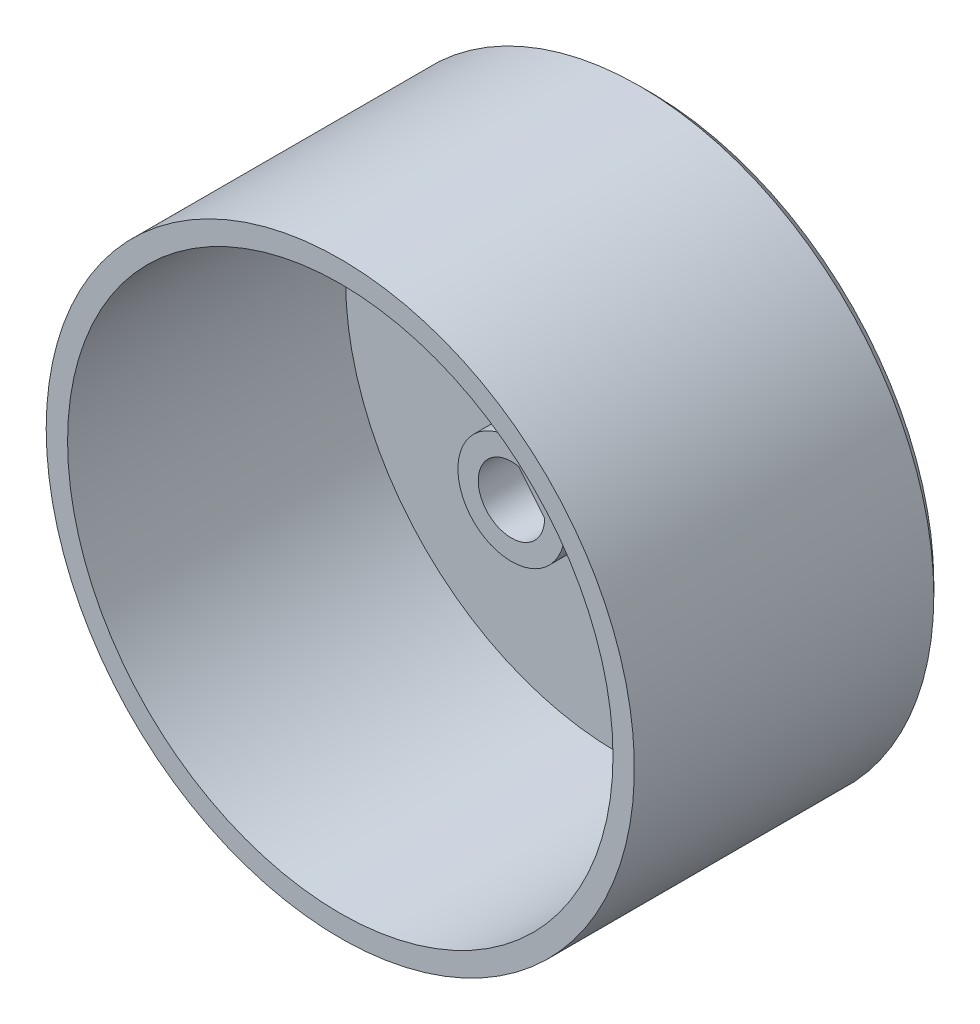
SolidWorks part; units mm, degrees
ref_plane "Front Plane" through (0, 0, 0) normal (0, 0, 1) x (1, 0, 0)
ref_plane "Top Plane" through (0, 0, 0) normal (0, 1, 0) x (1, 0, 0)
ref_plane "Right Plane" through (0, 0, 0) normal (1, 0, 0) x (0, 0, -1)
sketch "Sketch1" plane through (0, 0, 0) normal (0, 0, 1) x (1, 0, 0)
  circle A0 centre (0, 0) radius 27.5
  dimension "D1" = 55
extrude "Boss-Extrude1" add sketch "Sketch1" along normal blind 29
sketch "Sketch2" plane through (0, 0, 29) normal (0, 0, 1) x (1, 0, 0)
  circle A0 centre (0, 0) radius 25.5
  circle A1 centre (0, 0) radius 5
  circle A2 centre (0, 0) radius 27.5 construction
  dimension "D1" = 2
  dimension "D2" = 10
extrude "Cut-Extrude1" cut sketch "Sketch2" against normal blind 26
sketch "Sketch3" plane through (0, 0, 29) normal (0, 0, 1) x (1, 0, 0)
  line L0 (0.7101, 3.0176) -> (3.0993, 0.0643)
  arc A0 (0.7101, 3.0176) -> (3.0993, 0.0643) centre (0, 0) ccw
  dimension "D1" = 3.1
  dimension "D2" = 2.45
extrude "Cut-Extrude2" cut sketch "Sketch3" against normal up to surface (26 mm away) up to face at (5, 0, 3)
sketch "Sketch4" plane through (0, 0, 29) normal (0, 0, 1) x (1, 0, 0)
  circle A0 centre (0, 0) radius 5
extrude "Cut-Extrude3" cut sketch "Sketch4" against normal offset from surface (16 mm away) 10 up to face at (5, 0, 3)
chamfer "Chamfer1" distance 1 angle 45 1 edges at (27.5, 0, 0)
